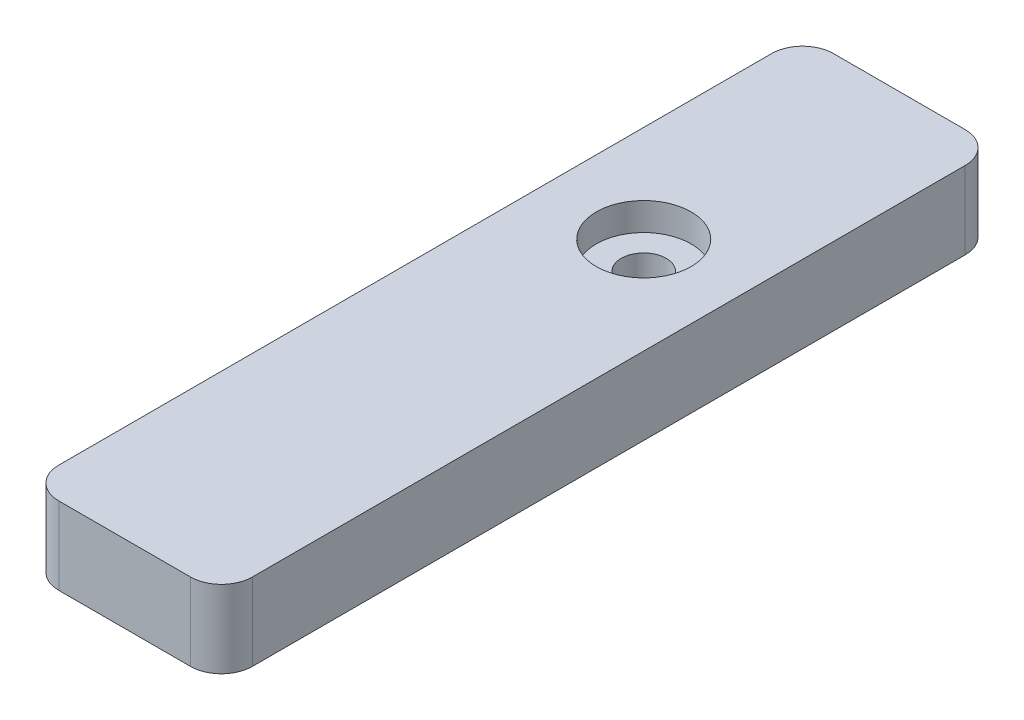
SolidWorks part; units mm, degrees
ref_plane "Front Plane" through (0, 0, 0) normal (0, 0, 1) x (1, 0, 0)
ref_plane "Top Plane" through (0, 0, 0) normal (0, 1, 0) x (1, 0, 0)
ref_plane "Right Plane" through (0, 0, 0) normal (1, 0, 0) x (0, 0, -1)
sketch "Sketch1" plane through (0, 0, 0) normal (0, 1, 0) x (1, 0, 0)
  line L1 (0, 0) -> (25, 0)
  line L2 (0, 0) -> (0, 100)
  line L3 (0, 100) -> (25, 100)
  line L4 (25, 0) -> (25, 100)
  dimension "D1" = 25
  dimension "D2" = 100
extrude "Boss-Extrude1" add sketch "Sketch1" along normal blind 10
hole_wizard "CBORE for M5 Hex Head Bolt1" positions "Sketch2" profile "Sketch3" counterbore size "M5" standard "ANSI Metric" end condition through all
sketch "Sketch2" plane through (0, 10, 0) normal (0, 1, 0) x (1, 0, 0)
  line L0 (25, 100) -> (0, 100) construction
  line L1 (0, 100) -> (0, 0) construction
  point P0 (12.5, 67)
  dimension "D1" = 33
  dimension "D2" = 12.5
sketch "Sketch3" plane through (12.5, 10, -67) normal (1, 0, 0) x (0, 0, 1)
  line L0 (0, 0) -> (0, 10)
  line L1 (0, 10) -> (2.9, 10)
  line L3 (2.9, 10) -> (2.9, 3.58)
  line L4 (2.9, 3.58) -> (6.12, 3.58)
  line L5 (6.12, 3.58) -> (6.12, 0)
  line L7 (6.12, 0) -> (0, 0)
  line L11 (0, -6.35) -> (0, 107.95) construction
  dimension "Thru Hole Dia." = 5.8
  dimension "Thru Hole Depth" = 10
  dimension "C'Bore Dia." = 12.24
  dimension "C'Bore Depth" = 3.58
fillet "Fillet1" radius 4 4 edges at (25, 5, 0) (0, 5, 0) (0, 5, -100) (25, 5, -100)
